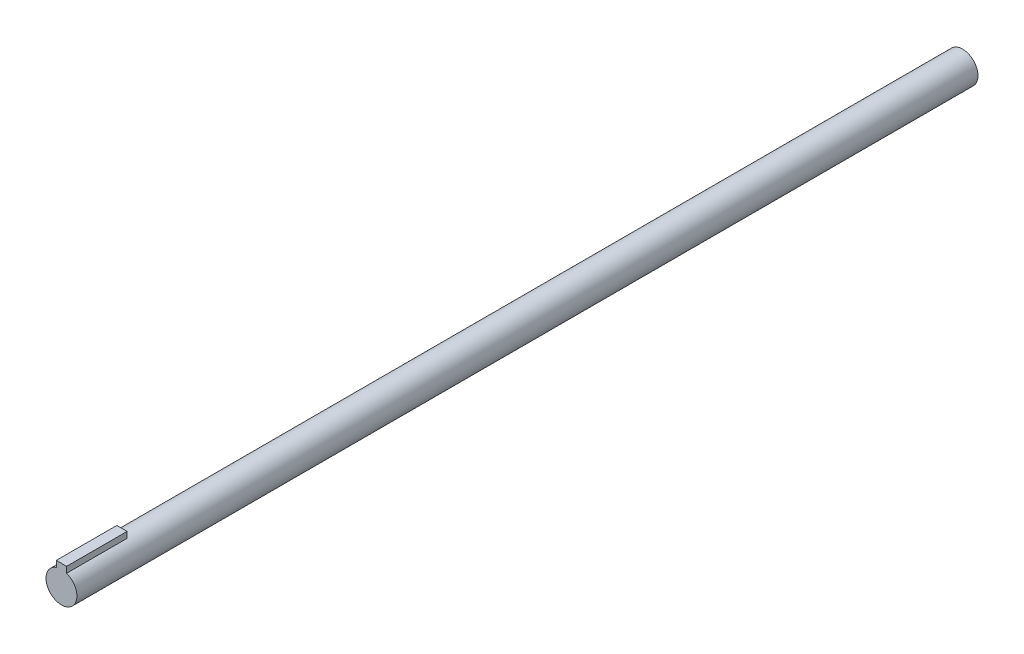
SolidWorks part; units mm, degrees
ref_plane "前视基准面" through (0, 0, 0) normal (0, 0, 1) x (1, 0, 0)
ref_plane "上视基准面" through (0, 0, 0) normal (0, 1, 0) x (1, 0, 0)
ref_plane "右视基准面" through (0, 0, 0) normal (1, 0, 0) x (0, 0, -1)
sketch "草图1" plane through (0, 0, 0) normal (0, 0, 1) x (1, 0, 0)
  circle A0 centre (0, 0) radius 6
extrude "凸台-拉伸1" add sketch "草图1" along normal blind 350 contours A0
sketch "草图2" plane through (0, 0, 350) normal (0, 0, 1) x (1, 0, 0)
  line L0 (0, 10.4071) -> (0, -11.7986) construction
  line L2 (-2, 8) -> (2, 8)
  line L3 (-2, 8) -> (-2, -1.1606)
  line L4 (-2, -1.1606) -> (2, -1.1606)
  line L5 (2, 8) -> (2, -1.1606)
  line L6 (-2, 8) -> (2, -1.1606) construction
  line L7 (-2, -1.1606) -> (2, 8) construction
  circle A1 centre (0, 0) radius 6 construction
  point P3 (0, 3.4197)
  dimension "D1" = 8
  dimension "D2" = 4
extrude "凸台-拉伸2" add sketch "草图2" against normal blind 23.51
